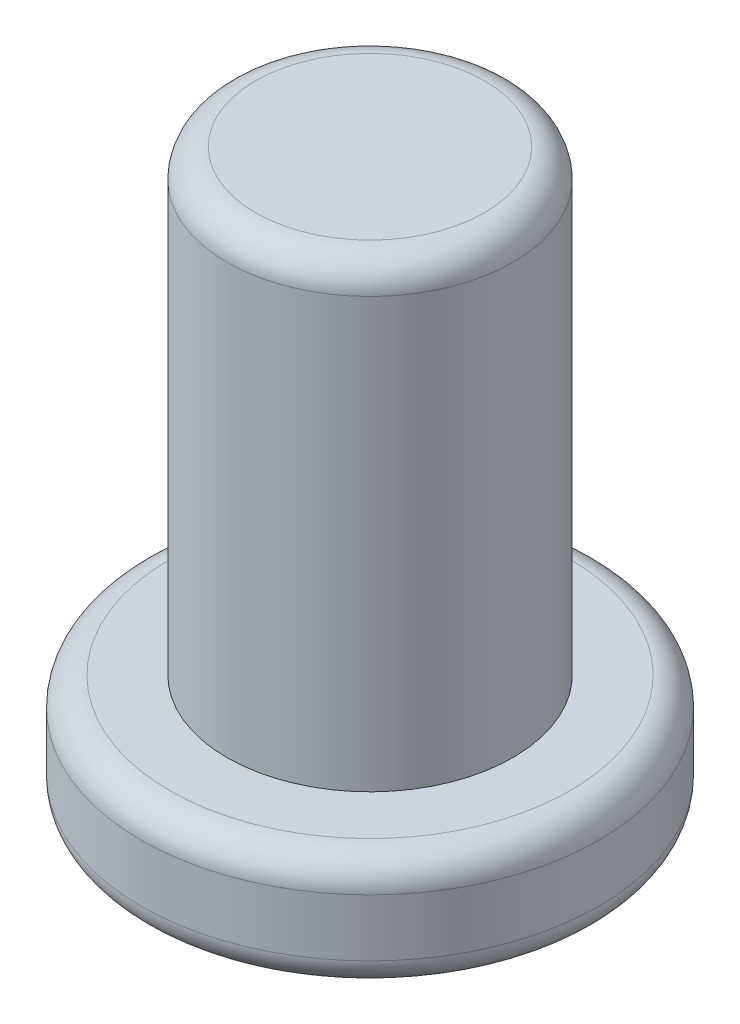
SolidWorks part; units mm, degrees
ref_plane "Front Plane" through (0, 0, 0) normal (0, 0, 1) x (1, 0, 0)
ref_plane "Top Plane" through (0, 0, 0) normal (0, 1, 0) x (1, 0, 0)
ref_plane "Right Plane" through (0, 0, 0) normal (1, 0, 0) x (0, 0, -1)
sketch "Sketch1" plane through (0, 0, 0) normal (0, 1, 0) x (1, 0, 0)
  circle A0 centre (0, 0) radius 4
  dimension "D1" = 8
extrude "Boss-Extrude1" add sketch "Sketch1" along normal blind 2
sketch "Sketch2" plane through (0, 2, 0) normal (0, 1, 0) x (1, 0, 0)
  circle A0 centre (0, 0) radius 2.5
  dimension "D1" = 5
extrude "Boss-Extrude2" add sketch "Sketch2" along normal blind 8
fillet "Fillet1" radius 0.5 1 edges at (0, 0, 4)
fillet "Fillet2" radius 0.5 1 edges at (0, 2, 4)
fillet "Fillet3" radius 0.5 1 edges at (0, 10, 2.5)
